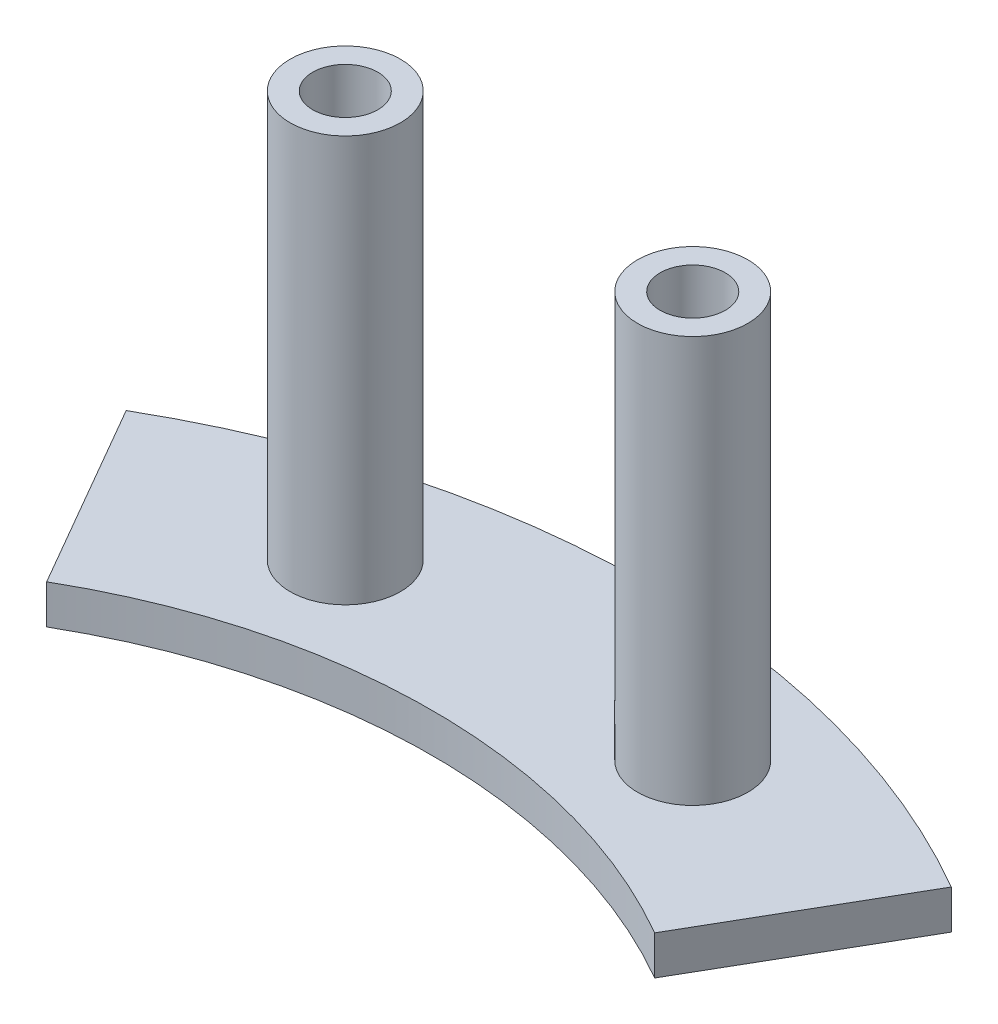
SolidWorks part; units mm, degrees
ref_plane "Front Plane" through (0, 0, 0) normal (0, 0, 1) x (1, 0, 0)
ref_plane "Top Plane" through (0, 0, 0) normal (0, 1, 0) x (1, 0, 0)
ref_plane "Right Plane" through (0, 0, 0) normal (1, 0, 0) x (0, 0, -1)
sketch "Sketch1" plane through (0, 0, 0) normal (0, 1, 0) x (1, 0, 0)
  line L0 (-14, 24.2487) -> (-19, 32.909) construction
  line L1 (14, 24.2487) -> (19, 32.909) construction
  line L2 (0, 0) -> (4, 0) construction
  line L3 (-19, 32.909) -> (-14, 24.2487)
  line L4 (19, 32.909) -> (14, 24.2487)
  circle A0 centre (0, 0) radius 28 construction
  circle A1 centre (0, 0) radius 38 construction
  arc A2 (-19, 32.909) -> (19, 32.909) centre (0, 0) cw
  arc A3 (-14, 24.2487) -> (14, 24.2487) centre (0, 0) cw
  arc A4 (-16.5, 28.5788) -> (16.5, 28.5788) centre (0, 0) cw construction
  dimension "D1" = 28
  dimension "D2" = 76
  dimension "D6" = 60
  dimension "D3" = 60
extrude "Boss-Extrude1" add sketch "Sketch1" along normal blind 1.8
sketch "Sketch2" plane through (0, 1.8, 0) normal (0, 1, 0) x (1, 0, 0)
  line L0 (-19, 32.909) -> (-14, 24.2487) construction
  line L2 (-8, 32) -> (8, 32) construction
  line L3 (0, 32) -> (0, 0) construction
  line L4 (14, 24.2487) -> (19, 32.909) construction
  arc A0 (-16.5, 28.5788) -> (16.5, 28.5788) centre (0, 0) cw construction
  circle A1 centre (-8, 32) radius 2.54
  circle A2 centre (8, 32) radius 2.54
  dimension "D1" = 5.08
  dimension "D2" = 8
  dimension "D3" = 32
extrude "Boss-Extrude2" add sketch "Sketch2" along normal blind 18.7
sketch "Sketch5" plane through (0, 20.5, 0) normal (0, 1, 0) x (1, 0, 0)
  circle A0 centre (-8, 32) radius 1.5
  circle A2 centre (8, 32) radius 1.5
  dimension "D1" = 3
extrude "Cut-Extrude1" cut sketch "Sketch5" against normal blind 3
